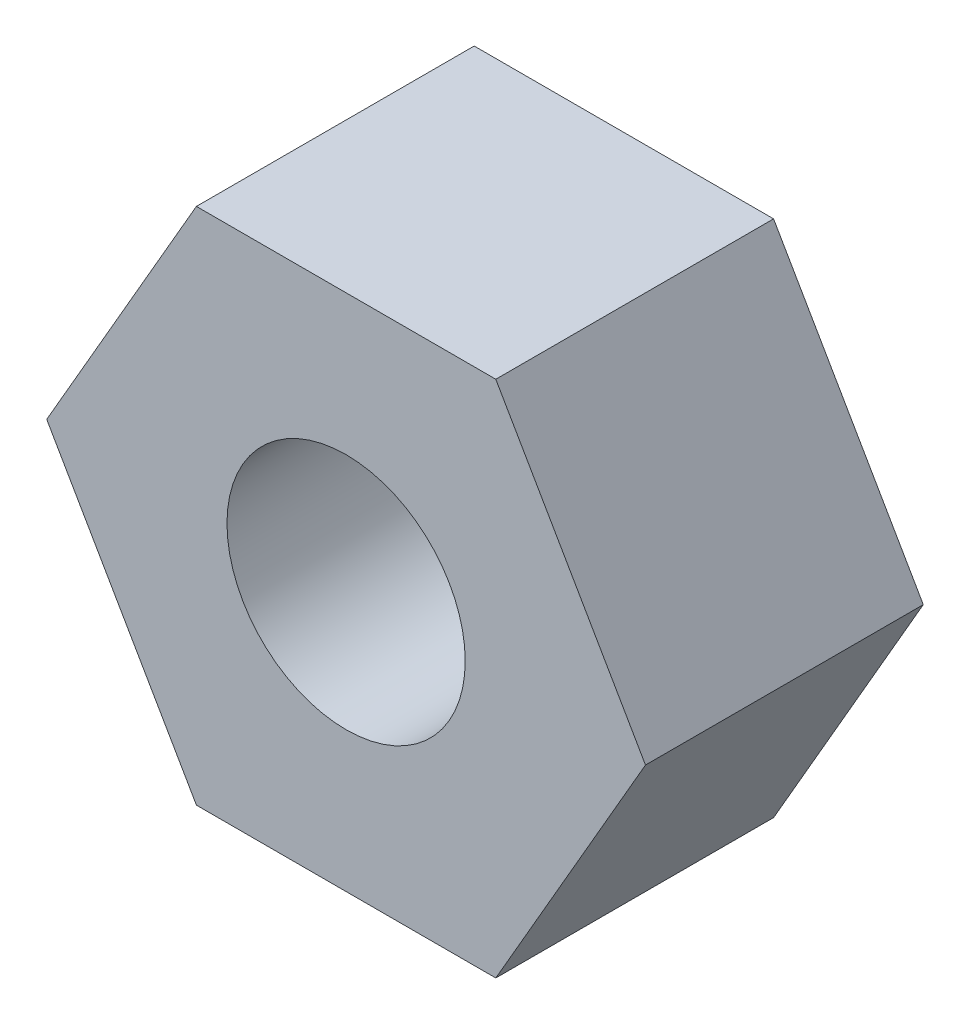
SolidWorks part; units mm, degrees
material "Nylon 6/10"
ref_plane "Front Plane" through (0, 0, 0) normal (0, 0, 1) x (1, 0, 0)
ref_plane "Top Plane" through (0, 0, 0) normal (0, 1, 0) x (1, 0, 0)
ref_plane "Right Plane" through (0, 0, 0) normal (1, 0, 0) x (0, 0, -1)
sketch "Sketch1" plane through (0, 0, 0) normal (0, 0, 1) x (1, 0, 0)
  line L1 (-3.2079, -5.5563) -> (3.2079, -5.5563)
  line L2 (3.2079, -5.5563) -> (6.4158, 0)
  line L3 (6.4158, 0) -> (3.2079, 5.5562)
  line L4 (3.2079, 5.5562) -> (-3.2079, 5.5563)
  line L5 (-3.2079, 5.5563) -> (-6.4158, 0)
  line L6 (-6.4158, 0) -> (-3.2079, -5.5563)
  circle A0 centre (0, 0) radius 5.5563 construction
  dimension "D1" = 11.1125
extrude "Boss-Extrude1" add sketch "Sketch1" along normal blind 5.9531
hole_wizard "1/4-20 Tapped Hole1" positions "Sketch3" profile "Sketch2" tap size "1/4-20" standard "ANSI Inch" end condition through all
sketch "Sketch3" plane through (0, 0, 5.9531) normal (0, 0, 1) x (1, 0, 0)
  point P0 (0, 0)
cosmetic thread "Hole Thread1" [suppressed] parameters "D2"=6.35
sketch "Sketch2" plane through (0, 0, 5.9531) normal (1, 0, 0) x (0, -1, 0)
  line L0 (0, 0) -> (0, 5.9531)
  line L1 (0, 5.9531) -> (2.5527, 5.9531)
  line L2 (2.5527, 5.9531) -> (2.5527, 0)
  line L5 (2.5527, 0) -> (0, 0)
  line L11 (0, -6.35) -> (0, 107.95) construction
  dimension "Thru Tap Drill Dia." = 5.1054
  dimension "Thru Tap Drill Depth" = 5.9531
